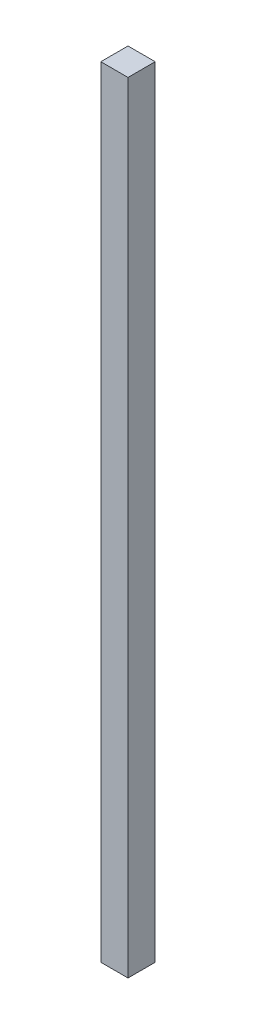
SolidWorks part; units mm, degrees
material "Pine"
ref_plane "Front Plane" through (0, 0, 0) normal (0, 0, 1) x (1, 0, 0)
ref_plane "Top Plane" through (0, 0, 0) normal (0, 1, 0) x (1, 0, 0)
ref_plane "Right Plane" through (0, 0, 0) normal (1, 0, 0) x (0, 0, -1)
sketch "Sketch1" plane through (0, 0, 0) normal (0, 1, 0) x (1, 0, 0)
  line L1 (0, 0) -> (38.1, 0)
  line L2 (0, 0) -> (0, 38.1)
  line L3 (0, 38.1) -> (38.1, 38.1)
  line L4 (38.1, 0) -> (38.1, 38.1)
  dimension "D1" = 38.1
  dimension "D2" = 38.1
extrude "Boss-Extrude1" add sketch "Sketch1" along normal blind 1092.2
